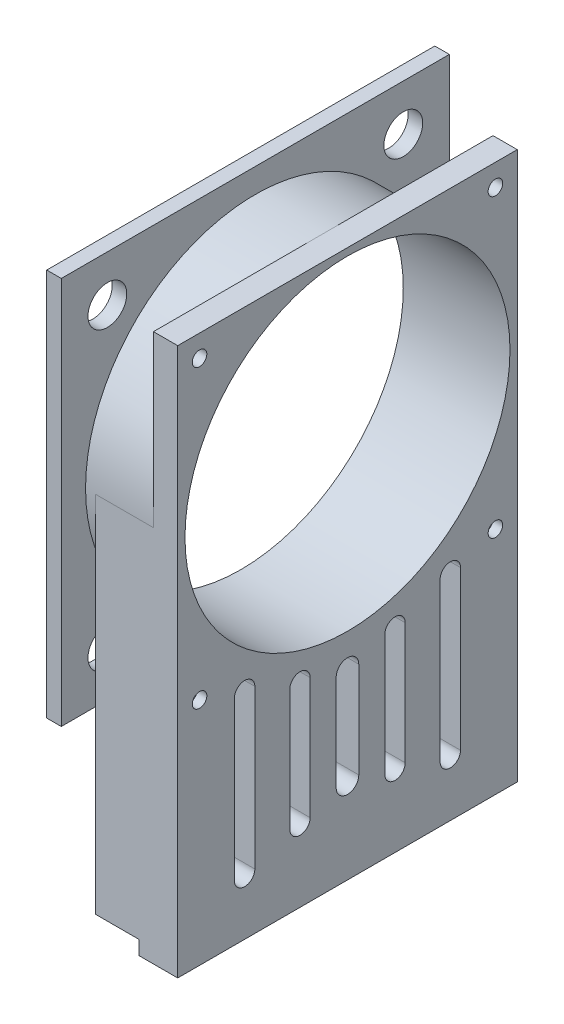
SolidWorks part; units mm, degrees
ref_plane "前视基准面" through (0, 0, 0) normal (0, 0, 1) x (1, 0, 0)
ref_plane "上视基准面" through (0, 0, 0) normal (0, 1, 0) x (1, 0, 0)
ref_plane "右视基准面" through (0, 0, 0) normal (1, 0, 0) x (0, 0, -1)
other "Configuration Table"
sketch "草图1" plane through (0, 0, 0) normal (1, 0, 0) x (0, 0, -1)
  circle A0 centre (0, 0) radius 33.5
  circle A1 centre (0, 0) radius 35
extrude "凸台-拉伸1" add sketch "草图1" along normal blind 22
sketch "草图2" plane through (22, 0, 0) normal (1, 0, 0) x (0, 0, -1)
  line L0 (0, -35) -> (0, -70)
  line L1 (0, -70) -> (35, -70)
  line L2 (35, -70) -> (35, 0)
  line L3 (0, -70) -> (-35, -70)
  line L4 (-35, -70) -> (-35, 0)
  circle A0 centre (0, 0) radius 35 construction
  arc A1 (-35, 0) -> (0, -35) centre (0, 0) ccw
  arc A2 (0, -35) -> (35, 0) centre (0, 0) ccw
  circle M5 centre (0, 0) radius 35
extrude "凸台-拉伸2" add sketch "草图2" against normal blind 17 contours L4 L3 L0 M5 | L1 L2 L0 M5
sketch "草图4" plane through (22, 0, 0) normal (1, 0, 0) x (0, 0, -1)
  line L5 (-35, 0) -> (-35, 35)
  line L6 (-35, 35) -> (35, 35)
  line L7 (35, 0) -> (35, 35)
  arc A2 (-35, 0) -> (0, 35) centre (0, 0) cw
  arc A3 (0, 35) -> (35, 0) centre (0, 0) cw
  point P0 (0, 0)
  point P1 (0, 0)
  arc M11 (35, 0) -> (-35, 0) centre (0, 0) ccw
extrude "凸台-拉伸3" add sketch "草图4" against normal blind 5 contours L7 L6 M11 | L6 L5 M11
sketch "草图9" plane through (0, -70, 0) normal (0, -1, 0) x (1, 0, 0)
  line L1 (5, 35) -> (22, 35)
  line L2 (5, 35) -> (5, -35)
  line L3 (5, -35) -> (22, -35)
  line L4 (22, 35) -> (22, -35)
  dimension "D1" = 70
  dimension "D2" = 17
extrude "凸台-拉伸4" add sketch "草图9" along normal blind 5
sketch "草图10" plane through (0, -75, 0) normal (0, -1, 0) x (1, 0, 0)
  line L1 (22, 35) -> (14, 35)
  line L2 (22, 35) -> (22, -35)
  line L3 (22, -35) -> (14, -35)
  line L4 (14, 35) -> (14, -35)
  line L5 (5, -35) -> (22, -35) construction
  dimension "D1" = 70
  dimension "D2" = 8
extrude "凸台-拉伸5" add sketch "草图10" along normal blind 2.9
sketch "草图12" plane through (0, 0, 0) normal (-1, 0, 0) x (0, 0, 1)
  line L1 (-40, -40) -> (40, -40)
  line L2 (-40, -40) -> (-40, 40)
  line L3 (-40, 40) -> (40, 40)
  line L4 (40, -40) -> (40, 40)
  line L5 (-40, -40) -> (40, 40) construction
  line L6 (-40, 40) -> (40, -40) construction
  circle A0 centre (0, 0) radius 35
  point P0 (0, 0)
  dimension "D1" = 80
extrude "凸台-拉伸7" add sketch "草图12" against normal blind 3
sketch "草图3" plane through (22, 0, 0) normal (1, 0, 0) x (0, 0, -1)
  line L1 (-30.5, -30.5) -> (30.5, -30.5)
  line L2 (-30.5, -30.5) -> (-30.5, 30.5)
  line L3 (-30.5, 30.5) -> (30.5, 30.5)
  line L4 (30.5, -30.5) -> (30.5, 30.5)
  circle A0 centre (-30.5, 30.5) radius 1.5
  circle A1 centre (-30.5, 30.5) radius 3
  circle A2 centre (30.5, 30.5) radius 1.5
  circle A3 centre (30.5, 30.5) radius 3
  circle A4 centre (-30.5, -30.5) radius 1.5
  circle A5 centre (-30.5, -30.5) radius 3
  circle A6 centre (30.5, -30.5) radius 1.5
  circle A7 centre (30.5, -30.5) radius 3
  point P0 (0, 0)
  dimension "D1" = 61
extrude "切除-拉伸1" cut sketch "草图3" against normal blind 30 contours L1 A4 L2 | L2 A4 L1 | L1 A6 L4 | L4 A6 L1 | A0 | A2
sketch "草图7" plane through (5, 0, 0) normal (-1, 0, 0) x (0, 0, 1)
  line L1 (-30.5, 30.5) -> (30.5, 30.5)
  line L2 (-30.5, 30.5) -> (-30.5, -30.5)
  line L3 (-30.5, -30.5) -> (30.5, -30.5)
  line L4 (30.5, 30.5) -> (30.5, -30.5)
  circle A0 centre (-30.5, -30.5) radius 3.25
  circle A1 centre (30.5, -30.5) radius 3.25
  dimension "D1" = 61
extrude "切除-拉伸3" cut sketch "草图7" against normal blind 15 contours L2 A0 L3 | L3 A0 L2 | L3 A1 L4 | L4 A1 L3
sketch "草图8" plane through (22, 0, 0) normal (1, 0, 0) x (0, 0, -1)
  line L0 (-21.2, -33.7813) -> (-21.2, -66.3892) construction
  line L1 (-19.1, -33.7813) -> (-19.1, -66.3892)
  line L2 (-23.3, -33.7813) -> (-23.3, -66.3892)
  line L3 (21.2, -33.7813) -> (21.2, -66.3892) construction
  line L4 (23.3, -33.7813) -> (23.3, -66.3892)
  line L5 (19.1, -33.7813) -> (19.1, -66.3892)
  line L6 (-9.8, -37.9207) -> (-9.8, -62.9207) construction
  line L7 (11.9, -37.9207) -> (11.9, -62.9207)
  line L8 (-7.7, -37.9207) -> (-7.7, -62.9207)
  line L9 (-11.9, -37.9207) -> (-11.9, -62.9207)
  line L10 (9.8, -37.9207) -> (9.8, -62.9207) construction
  line L11 (7.7, -37.9207) -> (7.7, -62.9207)
  line L12 (-9.8, -50.4207) -> (9.8, -50.4207)
  line L13 (0, -40.5404) -> (0, -60.301) construction
  line L15 (2.3269, -40.5404) -> (2.3269, -60.301)
  line L16 (-2.3269, -40.5404) -> (-2.3269, -60.301)
  arc A0 (-19.1, -33.7813) -> (-23.3, -33.7813) centre (-21.2, -33.7813) ccw
  arc A1 (-23.3, -66.3892) -> (-19.1, -66.3892) centre (-21.2, -66.3892) ccw
  circle A2 centre (-30.5, -30.5) radius 1.5 construction
  arc A3 (23.3, -33.7813) -> (19.1, -33.7813) centre (21.2, -33.7813) ccw
  arc A4 (19.1, -66.3892) -> (23.3, -66.3892) centre (21.2, -66.3892) ccw
  circle A5 centre (30.5, -30.5) radius 1.5 construction
  arc A6 (-7.7, -37.9207) -> (-11.9, -37.9207) centre (-9.8, -37.9207) ccw
  arc A7 (-11.9, -62.9207) -> (-7.7, -62.9207) centre (-9.8, -62.9207) ccw
  arc A8 (11.9, -37.9207) -> (7.7, -37.9207) centre (9.8, -37.9207) ccw
  arc A9 (7.7, -62.9207) -> (11.9, -62.9207) centre (9.8, -62.9207) ccw
  arc A10 (2.3269, -40.5404) -> (-2.3269, -40.5404) centre (0, -40.5404) ccw
  arc A11 (-2.3269, -60.301) -> (2.3269, -60.301) centre (0, -60.301) ccw
  point P2 (-21.2, -50.0853)
  point P7 (21.2, -50.0853)
  point P20 (9.8, -50.4207)
  point P22 (-9.8, -50.4207)
  point P37 (0, -50.4207)
  point P39 (0, -50.4207)
  dimension "D2" = 7.2
  dimension "D3" = 7.2
  dimension "D1" = 7.2
  dimension "D4" = 7.2
  dimension "D5" = 2.1
  dimension "D6" = 4.2
  dimension "D7" = 2.1
  dimension "D8" = 2.1
extrude "切除-拉伸4" cut sketch "草图8" against normal blind 30
sketch "草图13" plane through (0, 0, 0) normal (-1, 0, 0) x (0, 0, 1)
  circle A0 centre (-30.5, -30.5) radius 4
  circle A1 centre (30.5, -30.5) radius 4
  circle A2 centre (-30.5, 30.5) radius 4
  circle A3 centre (30.5, 30.5) radius 4
extrude "切除-拉伸5" cut sketch "草图13" against normal blind 3
